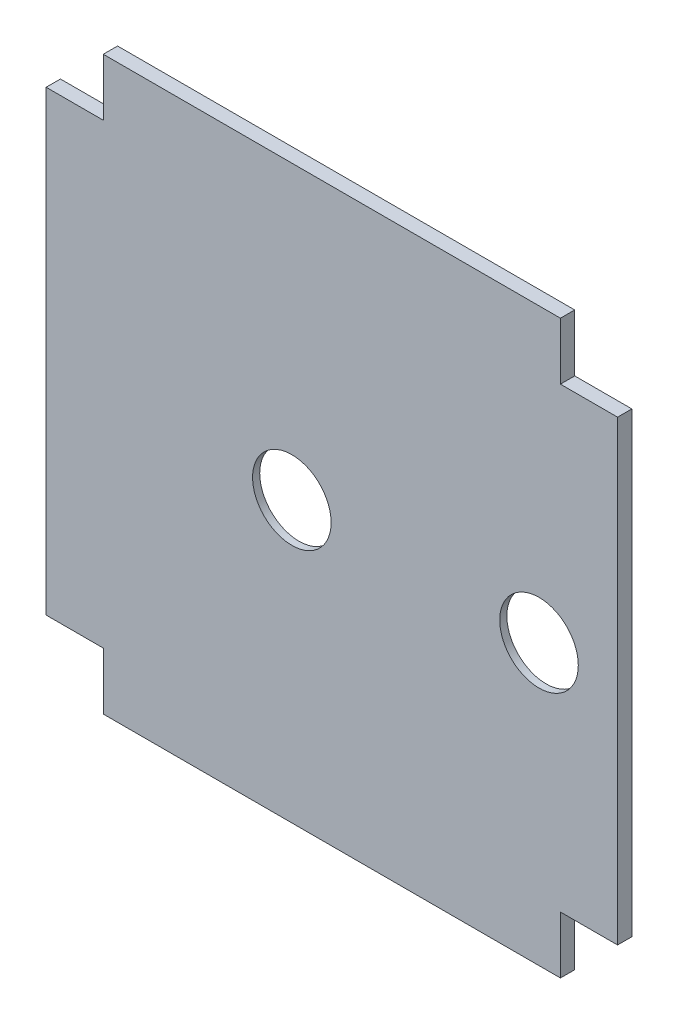
SolidWorks part; units mm, degrees
ref_plane "Front Plane" through (0, 0, 0) normal (0, 0, 1) x (1, 0, 0)
ref_plane "Top Plane" through (0, 0, 0) normal (0, 1, 0) x (1, 0, 0)
ref_plane "Right Plane" through (0, 0, 0) normal (1, 0, 0) x (0, 0, -1)
sketch "Sketch1" plane through (0, 0, 0) normal (0, 0, 1) x (1, 0, 0)
  line L1 (0, 0) -> (100, 0)
  line L2 (0, 0) -> (0, 100)
  line L3 (0, 100) -> (100, 100)
  line L4 (100, 0) -> (100, 100)
  dimension "D1" = 100
  dimension "D2" = 100
extrude "Boss-Extrude1" add sketch "Sketch1" along normal blind 2.5 contours L3 L4 L1 L2
sketch "Sketch2" plane through (0, 0, 2.5) normal (0, 0, 1) x (1, 0, 0)
  line L5 (0, 50) -> (12.5, 50) construction
  line L6 (0, 0) -> (0, 100) construction
  circle A1 centre (13.75, 50) radius 1.25
  dimension "D3" = 2.5
  dimension "D4" = 12.5
sketch "Sketch4" plane through (0, 0, 2.5) normal (0, 0, 1) x (1, 0, 0)
  line L0 (100, 50) -> (93.0433, 50) construction
  line L1 (100, 0) -> (100, 100) construction
  line L2 (86.25, 48.943) -> (43, 48.943) construction
  circle A0 centre (86.25, 48.943) radius 6.875
  circle A1 centre (43, 48.943) radius 6.875
  point P7 (100, 50)
  dimension "D2" = 13.75
  dimension "D3" = 43.25
  dimension "D1" = 13.75
extrude "Cut-Extrude2" cut sketch "Sketch4" against normal through all
sketch "Sketch5" plane through (0, 0, 0) normal (0, 0, -1) x (-1, 0, 0)
  circle A0 centre (-86.25, 48.943) radius 8.75
  circle A1 centre (-43, 48.943) radius 8.75
  dimension "D1" = 17.5
  dimension "D2" = 17.5
extrude "Cut-Extrude3" cut sketch "Sketch5" against normal blind 1.25
sketch "Sketch6" plane through (0, 0, 0) normal (0, 0, -1) x (-1, 0, 0)
  line L1 (-100, 100) -> (-90, 100)
  line L2 (-100, 100) -> (-100, 90)
  line L3 (-100, 90) -> (-90, 90)
  line L4 (-90, 100) -> (-90, 90)
  line L5 (-100, 0) -> (-90, 0)
  line L6 (-100, 0) -> (-100, 10)
  line L7 (-100, 10) -> (-90, 10)
  line L8 (-90, 0) -> (-90, 10)
  line L9 (0, 100) -> (-10, 100)
  line L10 (0, 100) -> (0, 90)
  line L11 (0, 90) -> (-10, 90)
  line L12 (-10, 100) -> (-10, 90)
  line L13 (0, 0) -> (-10, 0)
  line L14 (0, 0) -> (0, 10)
  line L15 (0, 10) -> (-10, 10)
  line L16 (-10, 0) -> (-10, 10)
  dimension "D1" = 10
extrude "Cut-Extrude4" cut sketch "Sketch6" against normal through all
